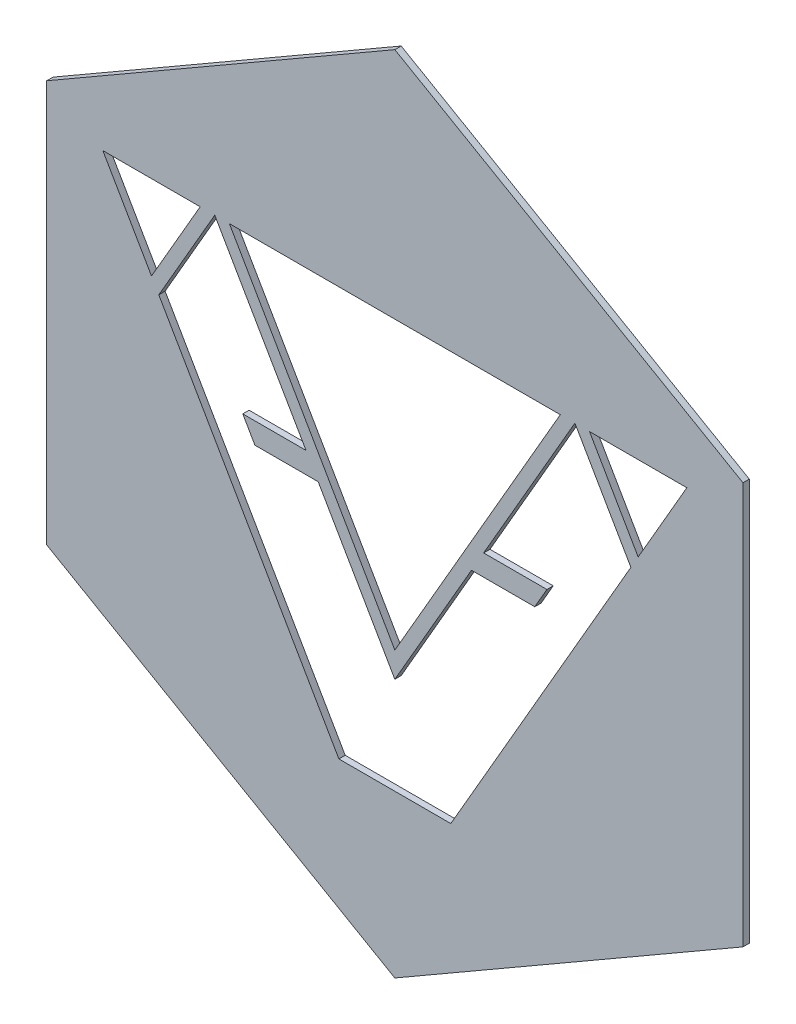
SolidWorks part; units mm, degrees
ref_plane "Front Plane" through (0, 0, 0) normal (0, 0, 1) x (1, 0, 0)
ref_plane "Top Plane" through (0, 0, 0) normal (0, 1, 0) x (1, 0, 0)
ref_plane "Right Plane" through (0, 0, 0) normal (1, 0, 0) x (0, 0, -1)
sketch "Sketch1" plane through (0, 0, 0) normal (0, 0, 1) x (1, 0, 0)
  line L0 (23.094, 13.3333) -> (15.396, 13.3333) construction
  line L1 (15.396, 13.3333) -> (19.245, 6.6667) construction
  line L2 (19.245, 6.6667) -> (23.094, 13.3333) construction
  line L3 (4.4264, -19) -> (18.6677, 5.6667) construction
  line L4 (18.6677, 5.6667) -> (14.2413, 13.3333) construction
  line L5 (14.2413, 13.3333) -> (7.0244, 0.8333) construction
  line L6 (27.5327, 15.896) -> (0, 31.792)
  line L7 (0, 31.792) -> (-27.5327, 15.896)
  line L8 (-27.5327, 15.896) -> (-27.5327, -15.896)
  line L9 (-27.5327, -15.896) -> (0, -31.792)
  line L10 (0, -31.792) -> (27.5327, -15.896)
  line L11 (27.5327, -15.896) -> (27.5327, 15.896)
  line L12 (27.5327, 15.896) -> (0, 31.792)
  line L13 (0, 31.792) -> (-27.5327, 15.896)
  line L14 (-27.5327, 15.896) -> (-27.5327, -15.896)
  line L15 (-27.5327, -15.896) -> (0, -31.792)
  line L16 (0, -31.792) -> (27.5327, -15.896)
  line L17 (27.5327, -15.896) -> (27.5327, 15.896)
  line L18 (7.0244, 0.8333) -> (12.0281, 0.8333) construction
  line L19 (12.0281, 0.8333) -> (11.0659, -0.8333) construction
  line L20 (11.0659, -0.8333) -> (6.0622, -0.8333) construction
  line L21 (6.0622, -0.8333) -> (0, -11.3333) construction
  line L22 (0, -11.3333) -> (-6.0622, -0.8333) construction
  line L23 (-6.0622, -0.8333) -> (-11.0659, -0.8333) construction
  line L24 (-11.0659, -0.8333) -> (-12.0281, 0.8333) construction
  line L25 (-12.0281, 0.8333) -> (-7.0244, 0.8333) construction
  line L26 (-7.0244, 0.8333) -> (-14.2413, 13.3333) construction
  line L27 (-14.2413, 13.3333) -> (-18.6677, 5.6667) construction
  line L28 (-18.6677, 5.6667) -> (-4.4264, -19) construction
  line L29 (-4.4264, -19) -> (4.4264, -19) construction
  line L30 (0, -9.3333) -> (13.0866, 13.3333) construction
  line L31 (13.0866, 13.3333) -> (-13.0866, 13.3333) construction
  line L32 (-13.0866, 13.3333) -> (0, -9.3333) construction
  line L33 (-23.094, 13.3333) -> (-19.245, 6.6667) construction
  line L34 (-19.245, 6.6667) -> (-15.396, 13.3333) construction
  line L35 (-15.396, 13.3333) -> (-23.094, 13.3333) construction
  line L36 (23.094, 13.3333) -> (15.396, 13.3333)
  line L37 (15.396, 13.3333) -> (19.245, 6.6667)
  line L38 (19.245, 6.6667) -> (23.094, 13.3333)
  line L39 (4.4264, -19) -> (18.6677, 5.6667)
  line L40 (18.6677, 5.6667) -> (14.2413, 13.3333)
  line L41 (14.2413, 13.3333) -> (7.0244, 0.8333)
  line L42 (7.0244, 0.8333) -> (12.0281, 0.8333)
  line L43 (12.0281, 0.8333) -> (11.0659, -0.8333)
  line L44 (11.0659, -0.8333) -> (6.0622, -0.8333)
  line L45 (6.0622, -0.8333) -> (0, -11.3333)
  line L46 (0, -11.3333) -> (-6.0622, -0.8333)
  line L47 (-6.0622, -0.8333) -> (-11.0659, -0.8333)
  line L48 (-11.0659, -0.8333) -> (-12.0281, 0.8333)
  line L49 (-12.0281, 0.8333) -> (-7.0244, 0.8333)
  line L50 (-7.0244, 0.8333) -> (-14.2413, 13.3333)
  line L51 (-14.2413, 13.3333) -> (-18.6677, 5.6667)
  line L52 (-18.6677, 5.6667) -> (-4.4264, -19)
  line L53 (-4.4264, -19) -> (4.4264, -19)
  line L54 (0, -9.3333) -> (13.0866, 13.3333)
  line L55 (13.0866, 13.3333) -> (-13.0866, 13.3333)
  line L56 (-13.0866, 13.3333) -> (0, -9.3333)
  line L57 (-23.094, 13.3333) -> (-19.245, 6.6667)
  line L58 (-19.245, 6.6667) -> (-15.396, 13.3333)
  line L59 (-15.396, 13.3333) -> (-23.094, 13.3333)
  dimension "D1" = 0
extrude "Boss-Extrude1" add sketch "Sketch1" along normal up to surface (0.5 mm away)
